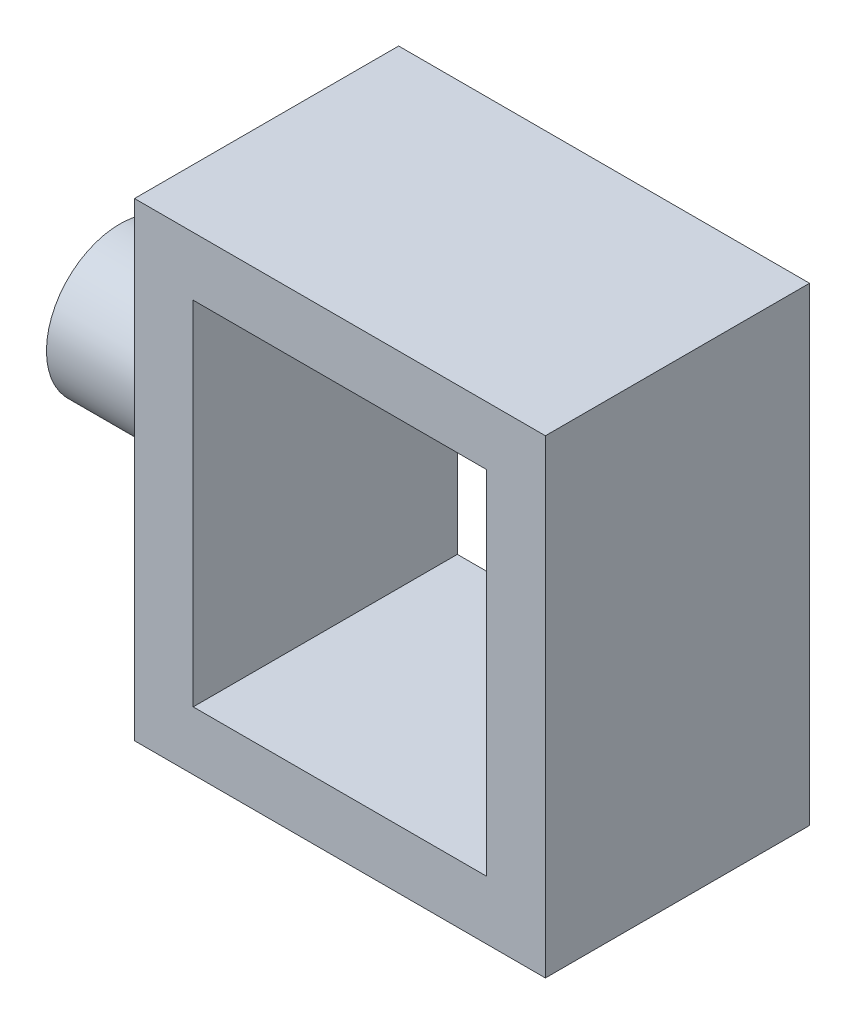
SolidWorks part; units mm, degrees
material "ABS"
ref_plane "Front Plane" through (0, 0, 0) normal (0, 0, 1) x (1, 0, 0)
ref_plane "Top Plane" through (0, 0, 0) normal (0, 1, 0) x (1, 0, 0)
ref_plane "Right Plane" through (0, 0, 0) normal (1, 0, 0) x (0, 0, -1)
sketch "Sketch1" plane through (0, 0, 0) normal (0, 0, 1) x (1, 0, 0)
  line L1 (0, 0) -> (-14, 0)
  line L2 (0, 0) -> (0, 16)
  line L3 (0, 16) -> (-14, 16)
  line L4 (-14, 0) -> (-14, 16)
  line L5 (-12, 14) -> (-2, 14)
  line L6 (-12, 14) -> (-12, 2)
  line L7 (-12, 2) -> (-2, 2)
  line L8 (-2, 14) -> (-2, 2)
  dimension "D1" = 14
  dimension "D2" = 16
  dimension "D3" = 10
  dimension "D4" = 12
  dimension "D5" = 2
  dimension "D6" = 2
extrude "Boss-Extrude1" add sketch "Sketch1" along normal blind 9
sketch "Sketch2" plane through (-14, 0, 0) normal (-1, 0, 0) x (0, 0, 1)
  line L0 (9, 16) -> (9, 0) construction
  line L1 (9, 16) -> (0, 16) construction
  circle A0 centre (4.5, 8) radius 2.5
  circle A1 centre (4.5, 8) radius 0.5
  dimension "D1" = 5
  dimension "D3" = 8
  dimension "D4" = 1
  dimension "D2" = 4.5
extrude "Boss-Extrude2" add sketch "Sketch2" along normal blind 5
equation "\".5c\"=0.25"
